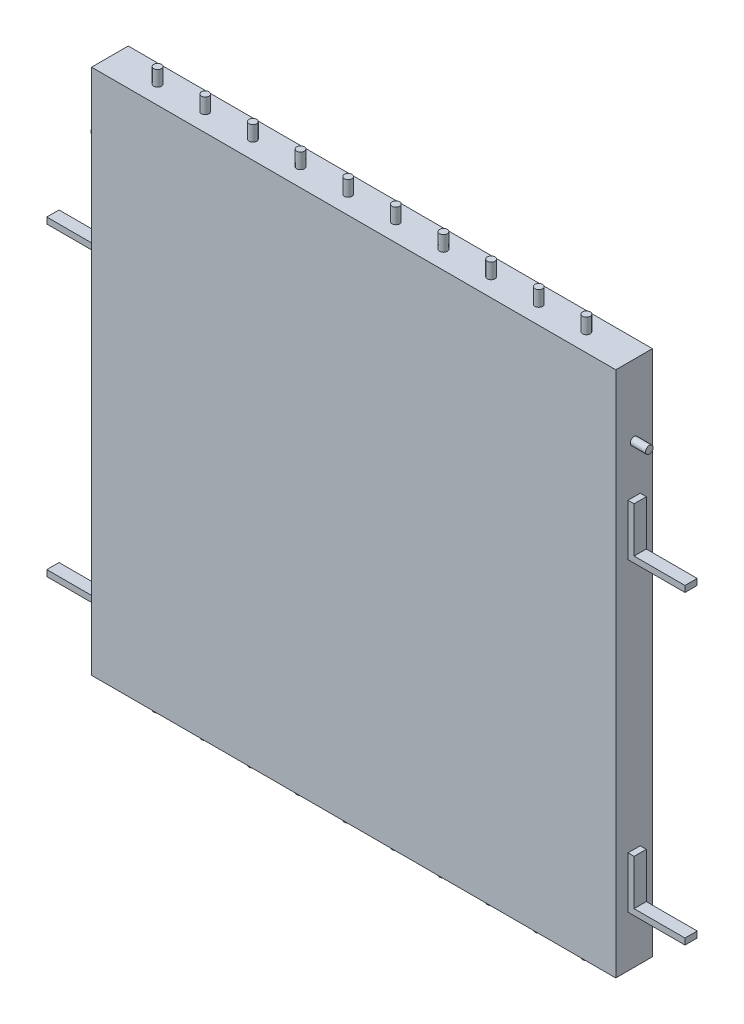
SolidWorks part; units mm, degrees
ref_plane "Front Plane" through (0, 0, 0) normal (0, 0, 1) x (1, 0, 0)
ref_plane "Top Plane" through (0, 0, 0) normal (0, 1, 0) x (1, 0, 0)
ref_plane "Right Plane" through (0, 0, 0) normal (1, 0, 0) x (0, 0, -1)
sketch "Sketch1" plane through (0, 0, 0) normal (0, 0, 1) x (1, 0, 0)
  line L1 (-515, -517.5) -> (515, -517.5)
  line L2 (-515, -517.5) -> (-515, 517.5)
  line L3 (-515, 517.5) -> (515, 517.5)
  line L4 (515, -517.5) -> (515, 517.5)
  line L5 (-515, -517.5) -> (515, 517.5) construction
  line L6 (-515, 517.5) -> (515, -517.5) construction
  point P0 (0, 0)
  dimension "D1" = 1030
  dimension "D2" = 1035
extrude "Boss-Extrude1" add sketch "Sketch1" along normal blind 72
sketch "Sketch2" plane through (515, 0, 0) normal (1, 0, 0) x (0, 0, -1)
  line L0 (-72, 517.5) -> (0, 517.5) construction
  line L1 (0, -517.5) -> (0, 517.5) construction
  circle A0 centre (-36, 378.5) radius 7.5
  dimension "D1" = 15
  dimension "D2" = 139
  dimension "D3" = 36
extrude "Boss-Extrude2" add sketch "Sketch2" along normal blind 30
sketch "Sketch3" plane through (515, 0, 0) normal (1, 0, 0) x (0, 0, -1)
  line L0 (-72, -517.5) -> (0, -517.5) construction
  line L1 (-48, 283.5) -> (-24, 283.5)
  line L2 (-48, 283.5) -> (-48, 182.5)
  line L3 (-48, 182.5) -> (-24, 182.5)
  line L4 (-24, 283.5) -> (-24, 182.5)
  line L5 (-48, 283.5) -> (-24, 182.5) construction
  line L6 (-48, 182.5) -> (-24, 283.5) construction
  line L7 (0, -517.5) -> (0, 517.5) construction
  point P0 (-36, 233)
  dimension "D1" = 101
  dimension "D2" = 700
  dimension "D3" = 24
  dimension "D4" = 36
extrude "Boss-Extrude3" add sketch "Sketch3" along normal blind 12
sketch "Sketch4" plane through (527, 0, 0) normal (1, 0, 0) x (0, 0, -1)
  line L0 (-48, 283.5) -> (-48, 182.5) construction
  line L1 (-24, 182.5) -> (-48, 182.5)
  line L2 (-24, 182.5) -> (-24, 194.5)
  line L3 (-24, 194.5) -> (-48, 194.5)
  line L4 (-48, 182.5) -> (-48, 194.5)
  dimension "D1" = 12
extrude "Boss-Extrude4" add sketch "Sketch4" along normal blind 100
pattern_linear "LPattern1" count 2 spacing 600 along (0, -1, 0) of "Boss-Extrude3", "Boss-Extrude4"
mirror "Mirror2" about plane through (0, 0, 0) normal (1, 0, 0) of "LPattern1", "Boss-Extrude4", "Boss-Extrude3", "Boss-Extrude2"
sketch "Sketch6" plane through (0, 517.5, 0) normal (0, 1, 0) x (1, 0, 0)
  line L1 (515, 0) -> (-515, 0) construction
  line L3 (515, -72) -> (515, 0) construction
  circle A0 centre (421.3636, -36) radius 7.5
  dimension "D1" = 15
  dimension "D2" = 36
  dimension "D3" = 93.6364
extrude "Boss-Extrude5" add sketch "Sketch6" along normal blind 30
pattern_linear "LPattern2" count 10 spacing 93.6364 along (-1, 0, 0) of "Boss-Extrude5"
mirror "Mirror3" about plane through (0, 0, 0) normal (0, 1, 0) of "Boss-Extrude5", "LPattern2"
